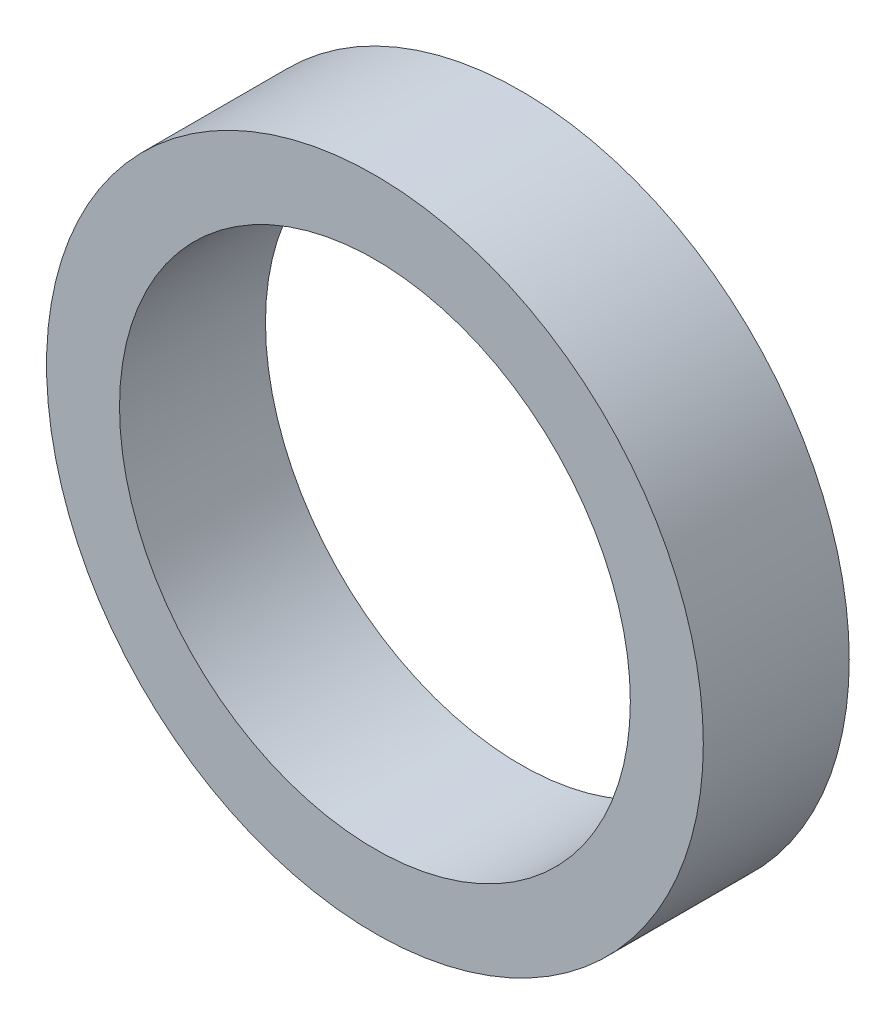
SolidWorks part; units mm, degrees
ref_plane "Vorne" through (0, 0, 0) normal (0, 0, 1) x (1, 0, 0)
ref_plane "Oben" through (0, 0, 0) normal (0, 1, 0) x (1, 0, 0)
ref_plane "Rechts" through (0, 0, 0) normal (1, 0, 0) x (0, 0, -1)
sketch "Skizze1" plane through (0, 0, 0) normal (0, 0, 1) x (1, 0, 0)
  circle A0 centre (0, 0) radius 7
  circle A1 centre (0, 0) radius 9
  dimension "D1" = 14
  dimension "D2" = 18
extrude "Aufsatz-Linear austragen1" add sketch "Skizze1" along normal blind 4
